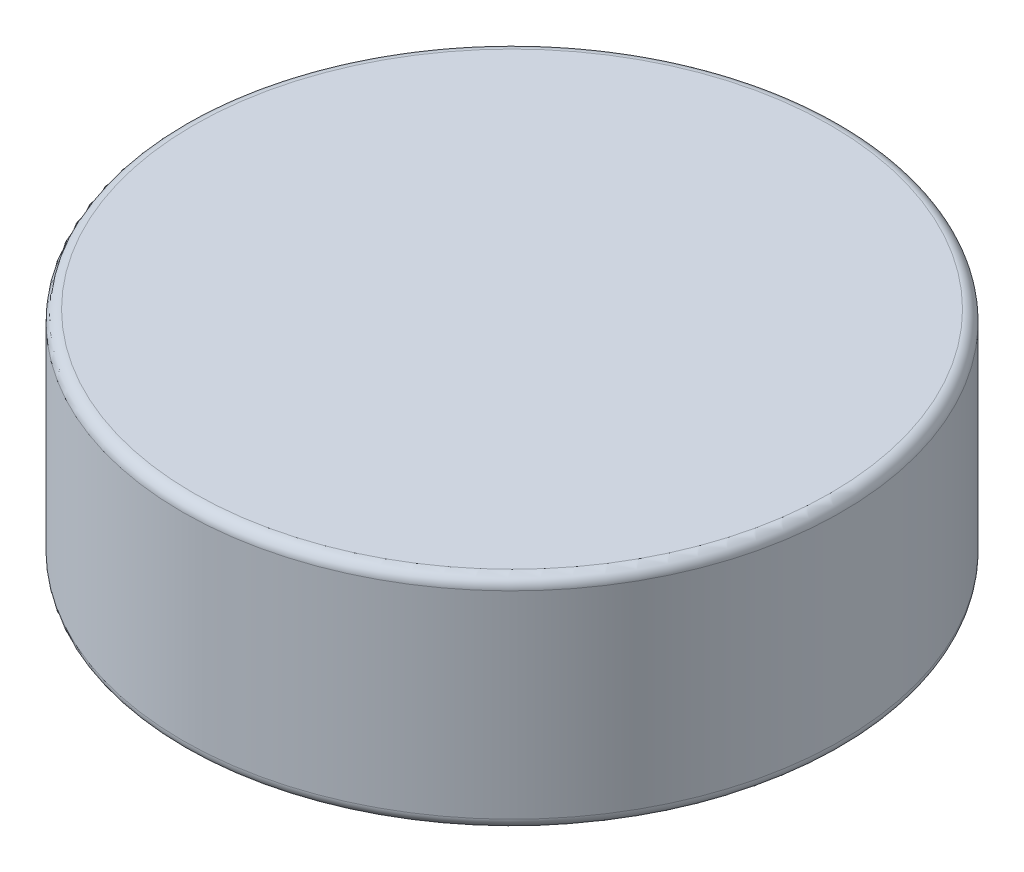
SolidWorks part; units mm, degrees
ref_plane "Front Plane" through (0, 0, 0) normal (0, 0, 1) x (1, 0, 0)
ref_plane "Top Plane" through (0, 0, 0) normal (0, 1, 0) x (1, 0, 0)
ref_plane "Right Plane" through (0, 0, 0) normal (1, 0, 0) x (0, 0, -1)
sketch "Sketch1" plane through (0, 0, 0) normal (0, 1, 0) x (1, 0, 0)
  circle A0 centre (0, 0) radius 15
  dimension "D1" = 30
extrude "Boss-Extrude1" add sketch "Sketch1" along normal blind 10
fillet "Fillet1" radius 0.5 2 edges at (0, 0, 15) (0, 10, 15)
